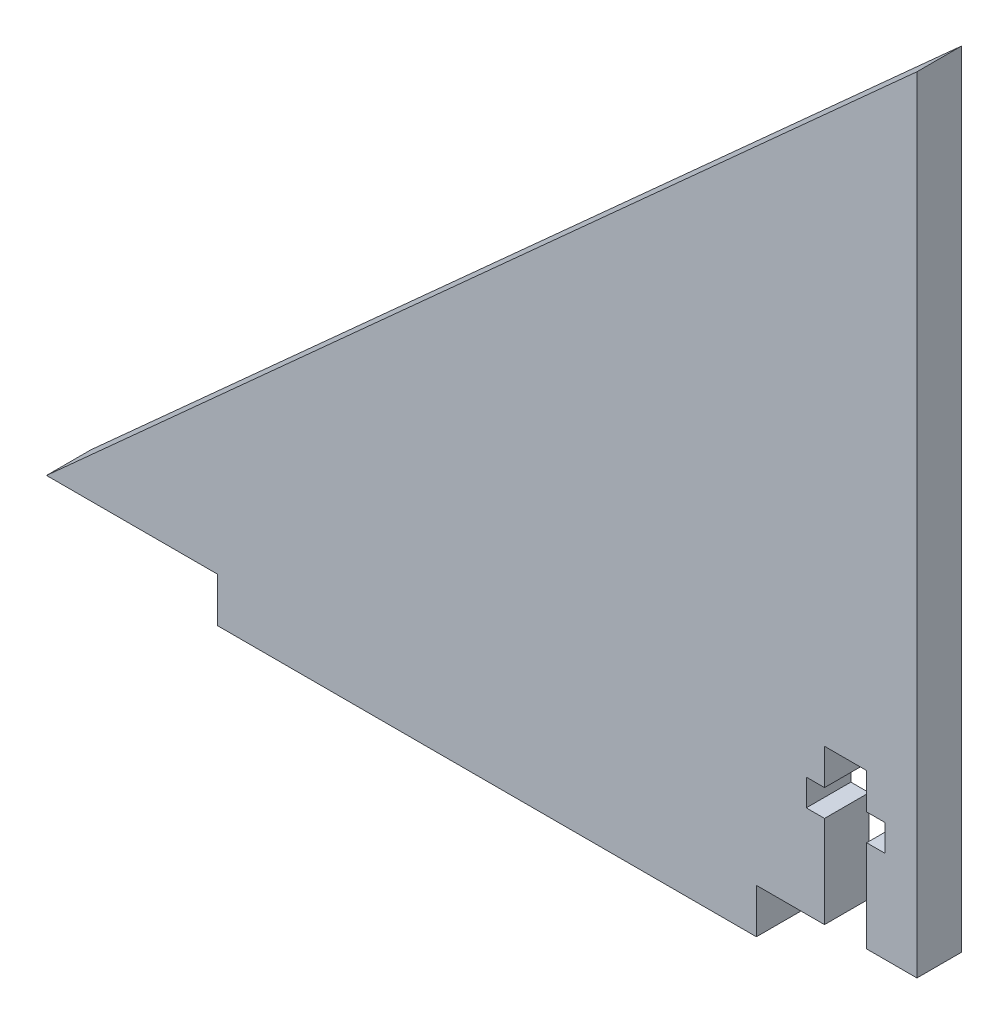
SolidWorks part; units mm, degrees
ref_plane "Front Plane" through (0, 0, 0) normal (0, 0, 1) x (1, 0, 0)
ref_plane "Top Plane" through (0, 0, 0) normal (0, 1, 0) x (1, 0, 0)
ref_plane "Right Plane" through (0, 0, 0) normal (1, 0, 0) x (0, 0, -1)
sketch "Sketch1" plane through (0, 0, 0) normal (0, 0, 1) x (1, 0, 0)
  line L0 (-61.976, 0) -> (-49.784, 0) construction
  line L1 (-61.976, 0) -> (0, 55.88)
  line L2 (0, 55.88) -> (0, 0)
  line L3 (0, 0) -> (-11.43, 0)
  line L5 (-49.784, 0) -> (-49.784, -3.175)
  line L6 (-49.784, -3.175) -> (-11.43, -3.175)
  line L7 (-11.43, 0) -> (-11.43, -3.175)
  line L8 (-49.784, 0) -> (-61.976, 0)
  line L9 (-11.43, 0) -> (0, 0) construction
  dimension "D1" = 3.175
  dimension "D2" = 38.354
  dimension "D3" = 11.43
  dimension "D4" = 55.88
  dimension "D5" = 12.192
extrude "Boss-Extrude1" add sketch "Sketch1" along normal blind 3.175
sketch "Sketch2" plane through (0, 0, 3.175) normal (0, 0, 1) x (1, 0, 0)
  line L0 (-3.58, 11) -> (-3.58, 8.45)
  line L1 (-3.58, 11) -> (-6.58, 11)
  line L2 (-3.58, 0) -> (-6.58, 0)
  line L3 (-6.58, 11) -> (-6.58, 8.45)
  line L4 (-3.58, 11) -> (-6.58, 0) construction
  line L5 (-3.58, 0) -> (-6.58, 11) construction
  line L6 (-6.58, 6.55) -> (-6.58, 0)
  line L7 (-7.88, 6.55) -> (-7.88, 8.45)
  line L8 (-7.88, 6.55) -> (-6.58, 6.55)
  line L9 (-2.28, 6.55) -> (-2.28, 8.45)
  line L10 (-7.88, 8.45) -> (-6.58, 8.45)
  line L11 (-7.88, 6.55) -> (-2.28, 8.45) construction
  line L12 (-2.28, 6.55) -> (-7.88, 8.45) construction
  line L13 (-3.58, 6.55) -> (-3.58, 0)
  line L14 (-6.58, 8.45) -> (-6.58, 6.55) construction
  line L15 (-3.58, 11) -> (-3.58, 6.55) construction
  line L16 (-3.58, 6.55) -> (-2.28, 6.55)
  line L17 (-3.58, 8.45) -> (-2.28, 8.45)
  line L18 (-6.58, 8.45) -> (-3.58, 8.45) construction
  line L19 (-3.58, 6.55) -> (-6.58, 6.55) construction
  line L20 (-11.43, 0) -> (0, 0) construction
  line L21 (-11.43, -3.175) -> (-11.43, 0) construction
  point P0 (-5.08, 0)
  point P5 (-5.08, 7.5)
  dimension "D1" = 3
  dimension "D2" = 11
  dimension "D3" = 5.6
  dimension "D4" = 1.9
  dimension "D5" = 3.5
  dimension "D6" = 6.35
extrude "Cut-Extrude1" cut sketch "Sketch2" against normal through all
